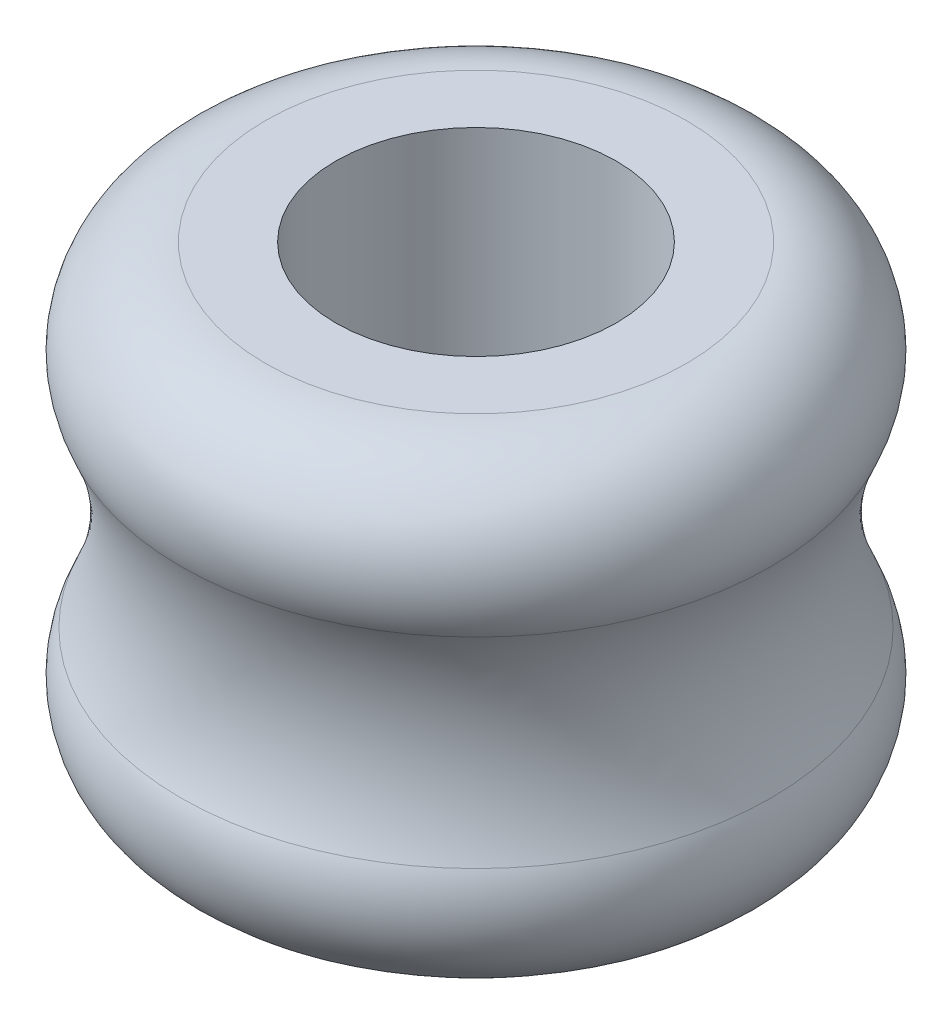
SolidWorks part; units mm, degrees
ref_plane "Plano frontal" through (0, 0, 0) normal (0, 0, 1) x (1, 0, 0)
ref_plane "Plano superior" through (0, 0, 0) normal (0, 1, 0) x (1, 0, 0)
ref_plane "Plano direito" through (0, 0, 0) normal (1, 0, 0) x (0, 0, -1)
sketch "Esboço1" plane through (0, 0, 0) normal (0, 0, 1) x (1, 0, 0)
  line L0 (0, 10) -> (0, 0) construction
  line L1 (0, 0) -> (0, 10) construction
  line L2 (0, 5) -> (-57.9736, 5) construction
  line L3 (0, 0) -> (-4.5, 0)
  line L4 (0, 10) -> (-4.5, 10)
  line L5 (0, 10) -> (0, 0)
  arc A0 (-6.307, 2.8571) -> (-6.307, 7.1429) centre (-10.8246, 5) ccw
  arc A1 (-4.5, 0) -> (-6.307, 2.8571) centre (-4.5, 2) cw
  arc A2 (-4.5, 10) -> (-6.307, 7.1429) centre (-4.5, 8) ccw
  point P8 (-69.1795, 22.39)
  point P9 (-68.4324, 23.8029)
  point P10 (-57.9736, 23.8029)
  point P11 (-70.1756, 0)
  point P12 (0, 0)
  dimension "D1" = 2
  dimension "D2" = 10
  dimension "D3" = 4.5
revolve "Revolução1" add sketch "Esboço1" angle 360 about L5
sketch "Esboço2" plane through (0, 0, 0) normal (0, -1, 0) x (1, 0, 0)
  circle A0 centre (0, 0) radius 3
  dimension "D1" = 6
extrude "Corte-extrusão1" cut sketch "Esboço2" against normal through all
